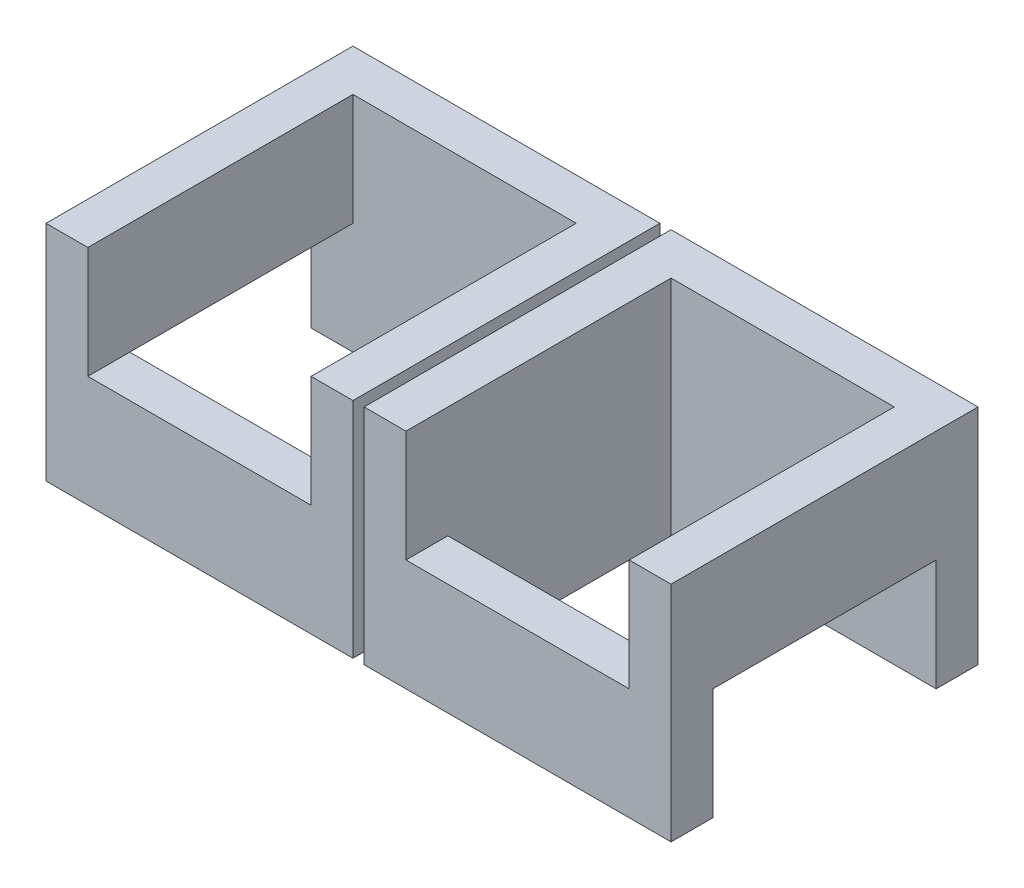
SolidWorks part; units mm, degrees
ref_plane "Front Plane" through (0, 0, 0) normal (0, 0, 1) x (1, 0, 0)
ref_plane "Top Plane" through (0, 0, 0) normal (0, 1, 0) x (1, 0, 0)
ref_plane "Right Plane" through (0, 0, 0) normal (1, 0, 0) x (0, 0, -1)
sketch "Sketch1" plane through (0, 0, 0) normal (0, 1, 0) x (1, 0, 0)
  line L1 (-50.8, -50.8) -> (50.8, -50.8)
  line L2 (-50.8, -50.8) -> (-50.8, 50.8)
  line L3 (-50.8, 50.8) -> (50.8, 50.8)
  line L4 (50.8, -50.8) -> (50.8, 50.8)
  line L5 (-50.8, -50.8) -> (50.8, 50.8) construction
  line L6 (-50.8, 50.8) -> (50.8, -50.8) construction
  point P0 (0, 0)
  dimension "D1" = 101.6
  dimension "D2" = 101.6
extrude "Extrude-Thin1" add sketch "Sketch1" along normal blind 101.6 thin
sketch "Sketch2" plane through (0, 101.6, 0) normal (0, 1, 0) x (1, 0, 0)
  line L0 (-69.85, -69.85) -> (69.85, -69.85) construction
  line L1 (-50.8, -50.8) -> (50.8, -50.8)
  line L2 (-50.8, -50.8) -> (-50.8, -69.85)
  line L3 (-50.8, -69.85) -> (50.8, -69.85)
  line L4 (50.8, -50.8) -> (50.8, -69.85)
ref_plane "Plane1" through (0, 50.8, 0) normal (0, 1, 0) x (1, 0, 0)
extrude "Cut-Extrude1" cut sketch "Sketch2" against normal up to surface (50.8 mm away)
sketch "Sketch3" plane through (0, 0, 0) normal (0, -1, 0) x (1, 0, 0)
  line L0 (-69.85, -69.85) -> (-69.85, 69.85) construction
  line L1 (-50.8, 50.8) -> (-69.85, 50.8)
  line L2 (-50.8, 50.8) -> (-50.8, -50.8)
  line L3 (-50.8, -50.8) -> (-69.85, -50.8)
  line L4 (-69.85, 50.8) -> (-69.85, -50.8)
extrude "Cut-Extrude2" cut sketch "Sketch3" against normal up to surface (50.8 mm away)
ref_plane "Plane2" through (72.39, 0, 0) normal (1, 0, 0) x (0, 0, -1)
mirror "Mirror2" about plane through (72.39, 0, 0) normal (1, 0, 0) of bodies 103
